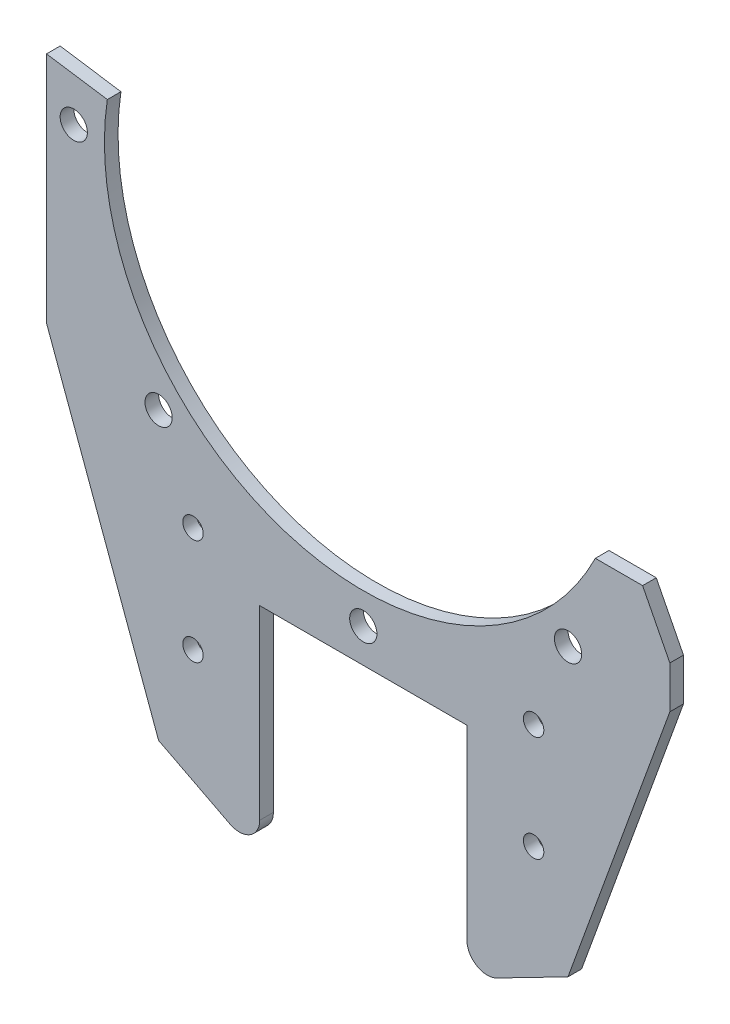
SolidWorks part; units mm, degrees
ref_plane "前视基准面" through (0, 0, 0) normal (0, 0, 1) x (1, 0, 0)
ref_plane "上视基准面" through (0, 0, 0) normal (0, 1, 0) x (1, 0, 0)
ref_plane "右视基准面" through (0, 0, 0) normal (1, 0, 0) x (0, 0, -1)
sketch "草图3" plane through (0, 0, 0) normal (0, 0, 1) x (1, 0, 0)
  line L38 (-46.5, 63) -> (-37.5766, 61.6567)
  line L102 (-46.5, 63) -> (-46.5, 28.7735)
  line L105 (34.0612, 39.1525) -> (41, 39.1525)
  line L150 (45, 25.1098) -> (45, 31.3171)
  line L151 (0, 13.5) -> (0, 8.5098) construction
  line L194 (45, 31.3171) -> (41, 39.1525)
  line L195 (0, 8.5098) -> (15.2, 8.5098)
  line L198 (0, 8.5098) -> (-15.2, 8.5098)
  line L200 (-15.2, 8.5098) -> (-15.2, -18.7762)
  line L207 (-30.0451, -16.0628) -> (-19.5711, -21.4445)
  line L209 (30.0451, -16.0628) -> (19.5711, -21.4445)
  line L211 (15.2, 8.5098) -> (15.2, -18.7762)
  line L212 (-46.5, 28.7735) -> (-30.0451, -16.0628)
  line L213 (30.0451, -16.0628) -> (45, 25.1098)
  arc A12 (-37.5766, 61.6567) -> (34.0612, 39.1525) centre (0, 56) ccw
  circle A17 centre (0, 13.5) radius 2
  circle A19 centre (-42.5, 56) radius 2
  circle A24 centre (30.052, 25.948) radius 2
  circle A25 centre (-30.052, 86.052) radius 2 [skipped]
  circle A26 centre (0, 98.5) radius 2 [skipped]
  circle A27 centre (30.052, 86.052) radius 2 [skipped]
  circle A28 centre (42.5, 56) radius 2 [skipped]
  circle A43 centre (-30.0451, 25.9549) radius 2
  circle A44 centre (-25, -1.9902) radius 1.5
  circle A45 centre (-25, 13.5098) radius 1.5
  circle A46 centre (-30.052, 25.948) radius 2 [skipped]
  circle A47 centre (25, 13.5098) radius 1.5
  circle A48 centre (25, -1.9902) radius 1.5
  arc A49 (-15.2, -18.7762) -> (-19.5711, -21.4445) centre (-18.2, -18.7762) cw
  arc A50 (15.2, -18.7762) -> (19.5711, -21.4445) centre (18.2, -18.7762) ccw
  circle A51 centre (0, 56) radius 42.5 construction
  point P23 (0, 0)
  point P24 (0, 0)
  point P25 (0, 0)
  dimension "D1" = 8
  dimension "D2" = 3
extrude "凸台-拉伸1" add sketch "草图3" along normal blind 2
